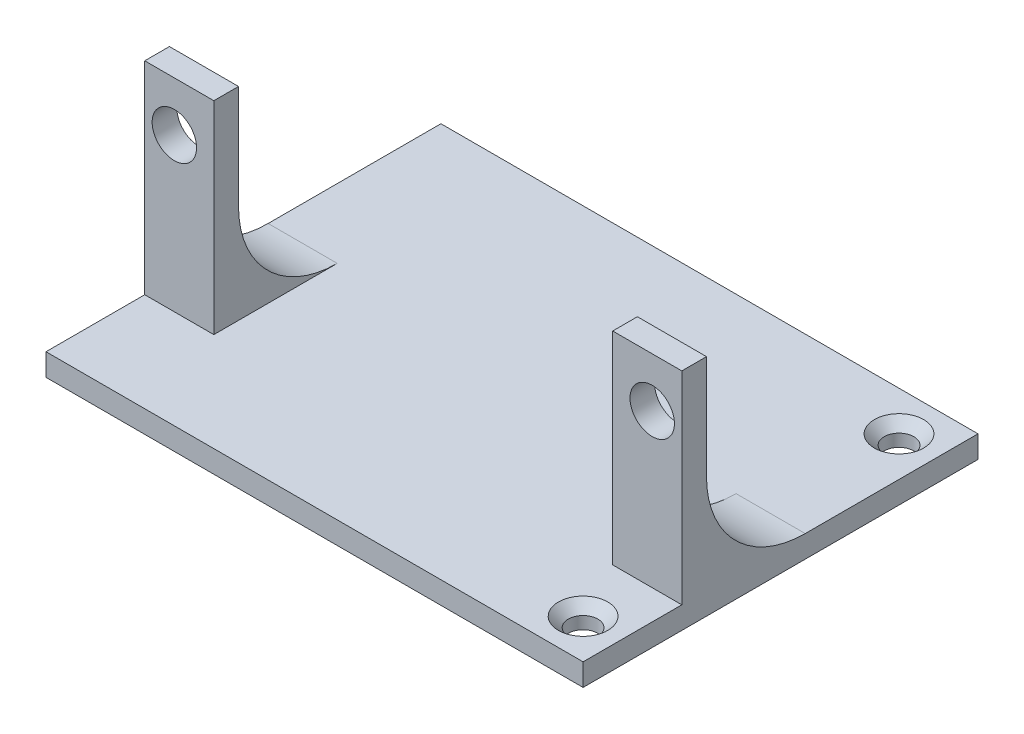
SolidWorks part; units mm, degrees
material "PLA"
ref_plane "Alzado" through (0, 0, 0) normal (0, 0, 1) x (1, 0, 0)
ref_plane "Planta" through (0, 0, 0) normal (0, 1, 0) x (1, 0, 0)
ref_plane "Vista lateral" through (0, 0, 0) normal (1, 0, 0) x (0, 0, -1)
sketch "Croquis1" plane through (0, 0, 0) normal (0, 1, 0) x (1, 0, 0)
  line L1 (3.5, 3.5) -> (-3.5, 3.5)
  line L2 (3.5, 3.5) -> (3.5, -3.5)
  line L3 (3.5, -3.5) -> (-3.5, -3.5)
  line L4 (-3.5, 3.5) -> (-3.5, -3.5)
  line L5 (3.5, 3.5) -> (-3.5, -3.5) construction
  line L6 (3.5, -3.5) -> (-3.5, 3.5) construction
  point P0 (0, 0)
  dimension "D1" = 7
  dimension "D2" = 7
extrude "Saliente-Extruir1" add sketch "Croquis1" along normal blind 3
sketch "Croquis2" plane through (0, 0, 3.5) normal (0, 0, 1) x (1, 0, 0)
  line L1 (3.5, 3) -> (3.5, 23.02)
  line L2 (3.5, 23.02) -> (-3.5, 23.02)
  line L3 (-3.5, 23.02) -> (-3.5, 3)
  line L4 (0.5, 23.02) -> (0.5, 3) construction
  line L5 (0.5, 18.01) -> (3.5, 18.01) construction
  line L7 (-3.5, 0) -> (3.5, 0) construction
  line L8 (-3.5, 3) -> (-3.5, 0) construction
  line L9 (3.5, 3) -> (3.5, 0) construction
  line L10 (-3.5, 0) -> (3.5, 0)
  line L11 (-3.5, 3) -> (-3.5, 0)
  line L12 (3.5, 3) -> (3.5, 0)
  circle A0 centre (0.5, 18.01) radius 2.25
  dimension "D5" = 5.01
  dimension "D3" = 4.5
  dimension "D1" = 3
  dimension "D2" = 23.02
  dimension "D7" = 3
extrude "Saliente-Extruir2" add sketch "Croquis2" along normal blind 2.5
sketch "Croquis3" plane through (0, 0, 0) normal (0, -1, 0) x (1, 0, 0)
  line L4 (-3.5, 6) -> (-3.5, -3.5)
  line L5 (-3.5, -3.5) -> (3.5, -3.5)
  line L6 (3.5, -3.5) -> (3.5, 6)
  line L7 (3.5, 6) -> (-3.5, 6)
  line L8 (-3.5, 6) -> (-3.5, -3.5)
  line L9 (-3.5, -3.5) -> (3.5, -3.5)
  line L10 (3.5, -3.5) -> (3.5, 6)
  line L11 (3.5, 6) -> (-3.5, 6)
  dimension "D1" = 0
extrude "Saliente-Extruir3" add sketch "Croquis3" along normal blind 2
sketch "Croquis4" plane through (0, 0, -3.5) normal (0, 0, -1) x (-1, 0, 0)
  line L4 (-3.5, 3) -> (-3.5, -2)
  line L5 (-3.5, -2) -> (3.5, -2)
  line L6 (3.5, -2) -> (3.5, 3)
  line L7 (3.5, 3) -> (-3.5, 3)
  line L8 (-3.5, 3) -> (-3.5, -2)
  line L9 (-3.5, -2) -> (3.5, -2)
  line L10 (3.5, -2) -> (3.5, 3)
  line L11 (3.5, 3) -> (-3.5, 3)
  dimension "D1" = 0
extrude "Saliente-Extruir4" add sketch "Croquis4" along normal blind 20.02
sketch "Croquis5" plane through (-3.5, 0, 0) normal (-1, 0, 0) x (0, 0, 1)
  line L0 (-23.52, 3) -> (6, 3)
  line L1 (6, 23.02) -> (6, -2) construction
  line L2 (6, 3) -> (6, -2)
  line L3 (6, -2) -> (-23.52, -2)
  line L4 (-23.52, -2) -> (-23.52, 3)
extrude "Saliente-Extruir5" add sketch "Croquis5" along normal blind 40.4
sketch "Croquis6" plane through (-43.9, 0, 0) normal (-1, 0, 0) x (0, 0, 1)
  line L1 (6, 3) -> (6, 23.02) construction
  line L2 (6, 23.02) -> (3.5, 23.02) construction
  line L3 (3.5, 23.02) -> (3.5, 3) construction
  line L4 (-23.52, 3) -> (-23.52, -2) construction
  line L5 (-23.52, -2) -> (6, -2) construction
  line L6 (6, -2) -> (6, 3) construction
  line L9 (6, 3) -> (6, 23.02)
  line L10 (6, 23.02) -> (3.5, 23.02)
  line L11 (3.5, 23.02) -> (3.5, 3)
  line L12 (-23.52, 3) -> (-23.52, -2)
  line L13 (-23.52, -2) -> (6, -2)
  line L14 (6, -2) -> (6, 3)
  line L16 (-23.52, 3) -> (3.5, 3)
extrude "Saliente-Extruir6" add sketch "Croquis6" along normal blind 7
sketch "Croquis7" plane through (0, 0, 6) normal (0, 0, 1) x (1, 0, 0)
  line L0 (-50.9, -2) -> (3.5, -2) construction
  line L1 (-23.7, -2) -> (-23.7, 3) construction
  line L2 (-43.9, 3) -> (-3.5, 3) construction
  circle A1 centre (0.5, 18.01) radius 2.25 construction
  circle A5 centre (-47.9, 18.01) radius 2.25
  dimension "D1" = 4.5
extrude "Cortar-Extruir1" cut sketch "Croquis7" against normal blind 4.5
sketch "Croquis8" plane through (0, 0, -23.52) normal (0, 0, -1) x (-1, 0, 0)
  line L4 (50.9, 3) -> (-3.5, 3)
  line L5 (-3.5, 3) -> (-3.5, -2)
  line L6 (-3.5, -2) -> (50.9, -2)
  line L7 (50.9, -2) -> (50.9, 3)
  line L8 (50.9, 3) -> (-3.5, 3)
  line L9 (-3.5, 3) -> (-3.5, -2)
  line L10 (-3.5, -2) -> (50.9, -2)
  line L11 (50.9, -2) -> (50.9, 3)
  dimension "D1" = 0
extrude "Saliente-Extruir7" add sketch "Croquis8" along normal blind 0.48
sketch "Croquis10" plane through (0, 3, 0) normal (0, 1, 0) x (1, 0, 0)
  line L8 (3.5, -3.5) -> (3.5, 24)
  line L9 (3.5, 24) -> (-50.9, 24)
  line L10 (-50.9, 24) -> (-50.9, -3.5)
  line L11 (-50.9, -3.5) -> (-43.9, -3.5)
  line L12 (-43.9, -3.5) -> (-43.9, -6)
  line L13 (-43.9, -6) -> (-3.5, -6)
  line L14 (-3.5, -6) -> (-3.5, -3.5)
  line L15 (-3.5, -3.5) -> (3.5, -3.5)
  line L16 (3.5, -3.5) -> (3.5, 24)
  line L17 (3.5, 24) -> (-50.9, 24)
  line L18 (-50.9, 24) -> (-50.9, -3.5)
  line L19 (-50.9, -3.5) -> (-43.9, -3.5)
  line L20 (-43.9, -3.5) -> (-43.9, -6)
  line L21 (-43.9, -6) -> (-3.5, -6)
  line L22 (-3.5, -6) -> (-3.5, -3.5)
  line L23 (-3.5, -3.5) -> (3.5, -3.5)
  dimension "D1" = 0
extrude "Cortar-Extruir3" cut sketch "Croquis10" against normal blind 0.5
sketch "Croquis11" plane through (0, 0, 6) normal (0, 0, 1) x (1, 0, 0)
  line L0 (-23.7, -2) -> (-23.7, 2.5) construction
  line L1 (3.5, -2) -> (-50.9, -2) construction
  line L2 (-43.9, 2.5) -> (-3.5, 2.5) construction
  line L4 (3.5, 2.5) -> (-50.9, 2.5)
  line L5 (3.5, 2.5) -> (3.5, -2)
  line L6 (3.5, -2) -> (-50.9, -2)
  line L7 (-50.9, 2.5) -> (-50.9, -2)
  line L8 (3.5, 2.5) -> (-50.9, -2) construction
  line L9 (3.5, -2) -> (-50.9, 2.5) construction
  point P6 (-23.7, 0.25)
extrude "Saliente-Extruir9" add sketch "Croquis11" along normal blind 10
sketch "Croquis12" plane through (0, -2, 0) normal (0, -1, 0) x (1, 0, 0)
  line L1 (-50.9, 16) -> (3.5, 16) construction
  line L2 (3.5, -24) -> (-50.9, -24) construction
  line L3 (-0.5, 16) -> (-0.5, 12) construction
  line L6 (3.5, -24) -> (3.5, 16) construction
  line L7 (3.5, -20) -> (-0.5, -20) construction
  line L9 (-0.5, 12) -> (3.5, 12) construction
  line L10 (-0.5, -20) -> (-0.5, -24) construction
  circle A1 centre (-0.5, 12) radius 1.5
  circle A2 centre (-0.5, -20) radius 1.5
  dimension "D5" = 3
  dimension "D7" = 3
  dimension "D1" = 4
  dimension "D2" = 4
  dimension "D3" = 4
  dimension "D4" = 4
extrude "Cortar-Extruir4" cut sketch "Croquis12" against normal through all
chamfer "Chaflán1" distance 1 angle 45 2 edges at (-0.5, 2.5, 13.5) (-0.5, 2.5, -18.5)
sketch "Croquis13" plane through (0, 0, 16) normal (0, 0, 1) x (1, 0, 0)
  line L1 (-50.9, -2) -> (3.5, -2) construction
  line L3 (-23.7, 0.25) -> (-23.7, -2) construction
  line L4 (3.5, 0.25) -> (-50.9, 0.25)
  line L5 (3.5, 0.25) -> (3.5, -2)
  line L6 (3.5, -2) -> (-50.9, -2)
  line L7 (-50.9, 0.25) -> (-50.9, -2)
  line L8 (3.5, 0.25) -> (-50.9, -2) construction
  line L9 (3.5, -2) -> (-50.9, 0.25) construction
  point P1 (-23.7, -0.875)
  dimension "D1" = 2.25
extrude "Cortar-Extruir5" cut sketch "Croquis13" against normal through all
fillet "Redondeo1" radius 10 2 edges at (-47.4, 2.5, 3.5) (0, 2.5, 3.5)
